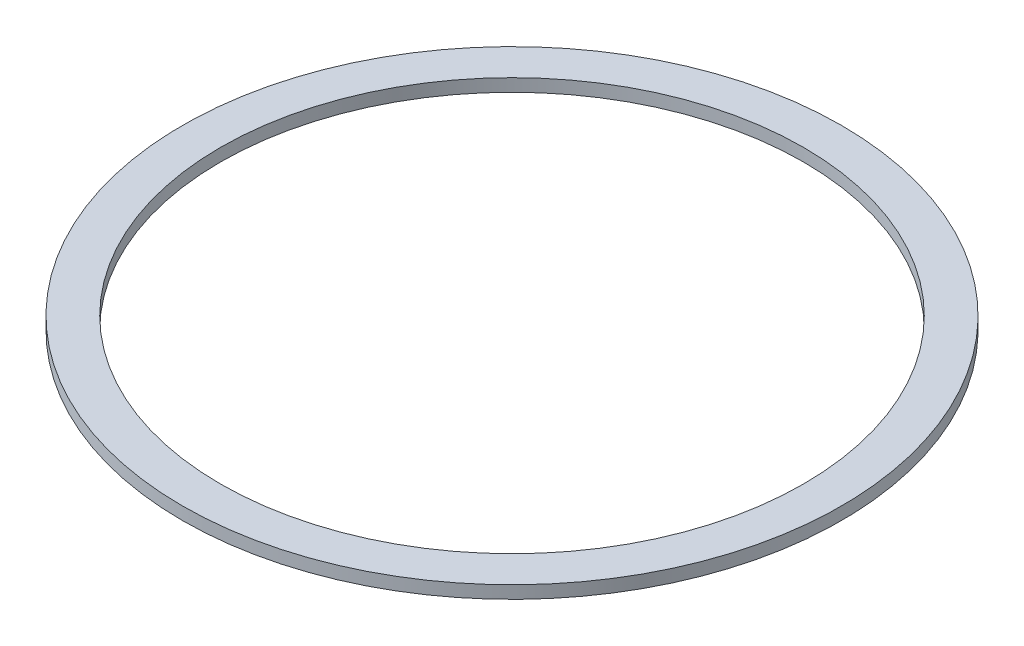
SolidWorks part; units mm, degrees
material "Silicon Rubber"
ref_plane "Front Plane" through (0, 0, 0) normal (0, 0, 1) x (1, 0, 0)
ref_plane "Top Plane" through (0, 0, 0) normal (0, 1, 0) x (1, 0, 0)
ref_plane "Right Plane" through (0, 0, 0) normal (1, 0, 0) x (0, 0, -1)
sketch "Sketch1" plane through (0, 0, 0) normal (0, 1, 0) x (1, 0, 0)
  circle A0 centre (0, 0) radius 33.02
  circle A1 centre (0, 0) radius 29.21
  point P5 (0, 0.1192)
  point P6 (0.0045, 0)
  dimension "D1" = 66.04
  dimension "D2" = 58.42
extrude "Boss-Extrude1" add sketch "Sketch1" along normal blind 1.27
